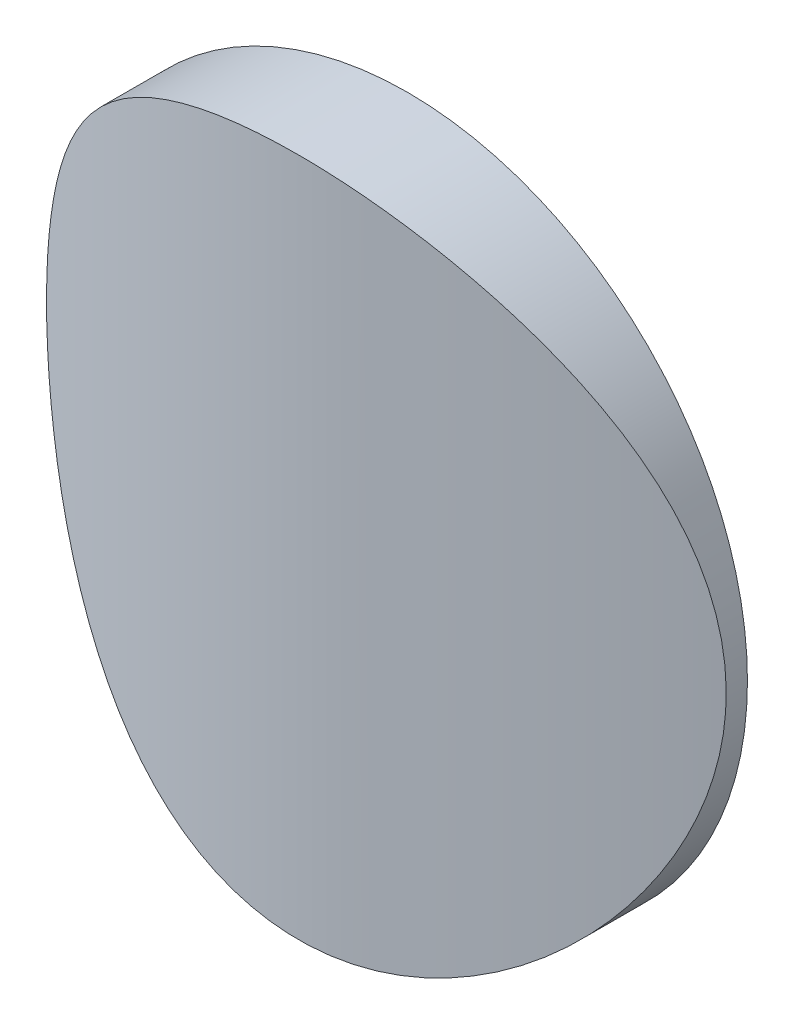
SolidWorks part; units mm, degrees
ref_plane "Front Plane" through (0, 0, 0) normal (0, 0, 1) x (1, 0, 0)
ref_plane "Top Plane" through (0, 0, 0) normal (0, 1, 0) x (1, 0, 0)
ref_plane "Right Plane" through (0, 0, 0) normal (1, 0, 0) x (0, 0, -1)
sketch "Sketch1" plane through (0, 0, 0) normal (0, 0, 1) x (1, 0, 0)
  circle A0 centre (0, 0) radius 25.4
  dimension "D1" = 50.8
extrude "Boss-Extrude1" add sketch "Sketch1" along normal blind 25.4
sketch "Sketch4" plane through (0, 0, 0) normal (0, 1, 0) x (0, 0, -1)
  circle A1 centre (44.45, 0) radius 52.578 construction
  circle A3 centre (44.45, 0) radius 52.578
extrude "Cut-Extrude3" cut sketch "Sketch4" against normal through all both and the other way through all flip side to cut
